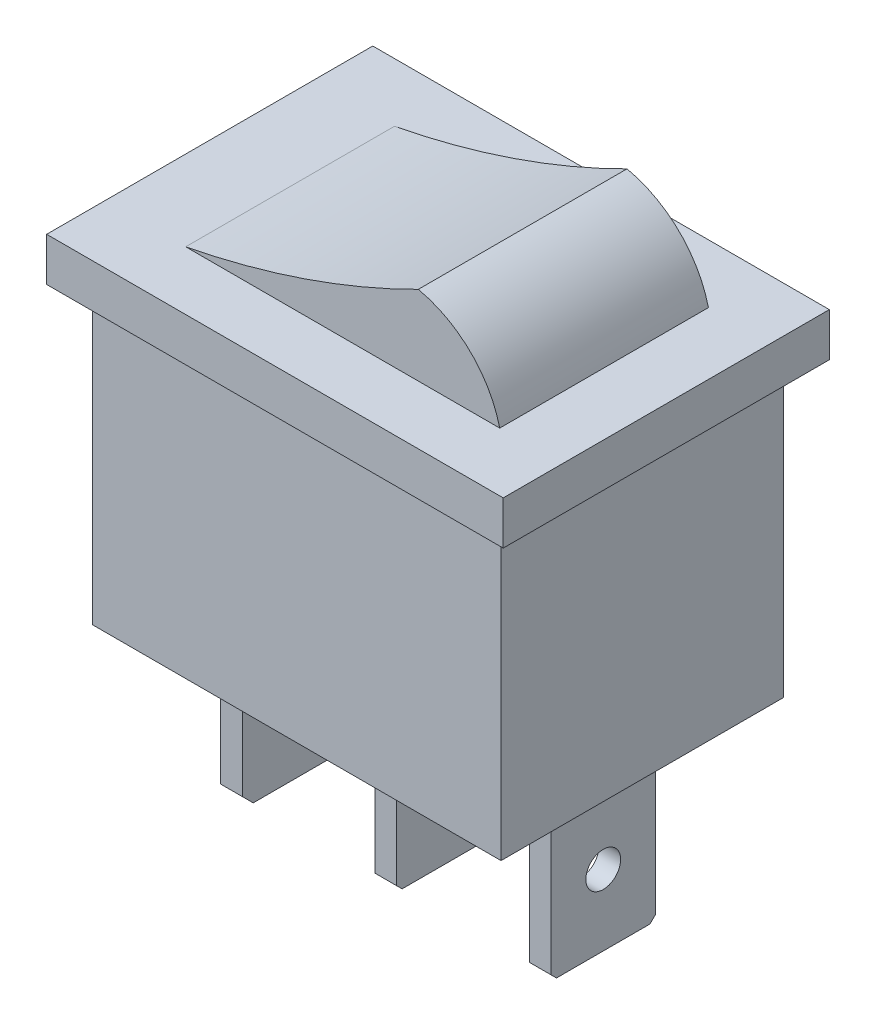
SolidWorks part; units mm, degrees
ref_plane "Front Plane" through (0, 0, 0) normal (0, 0, 1) x (1, 0, 0)
ref_plane "Top Plane" through (0, 0, 0) normal (0, 1, 0) x (1, 0, 0)
ref_plane "Right Plane" through (0, 0, 0) normal (1, 0, 0) x (0, 0, -1)
ref_plane "Plane4" through (0, 0, -4.8) normal (0, 0, -1) x (-1, 0, 0)
sketch "Sketch1" plane through (0, 0, -4.8) normal (0, 0, -1) x (-1, 0, 0)
  line L0 (-7.6394, 15.5) -> (6.8039, 15.5)
  arc A0 (-3.8941, 19.1536) -> (-7.6394, 15.5) centre (-2.8428, 14.3295) ccw
  arc A1 (6.8039, 15.5) -> (-3.8941, 19.1536) centre (14.6611, 55.995) cw
extrude "Boss-Extrude1" add sketch "Sketch1" against normal blind 9.6
ref_plane "Plane5" through (0, 15.5, 0) normal (0, 1, 0) x (1, 0, 0)
sketch "Sketch2" plane through (0, 15.5, 0) normal (0, 1, 0) x (1, 0, 0)
  line L0 (10.5, -7.5) -> (10.5, 7.5)
  line L1 (10.5, 7.5) -> (-10.5, 7.5)
  line L2 (-10.5, 7.5) -> (-10.5, -7.5)
  line L3 (-10.5, -7.5) -> (10.5, -7.5)
extrude "Boss-Extrude2" add sketch "Sketch2" against normal blind 2
sketch "Sketch3" plane through (0, 13.5, 0) normal (0, -1, 0) x (1, 0, 0)
  line L0 (9.4, 6.5) -> (9.4, -6.5)
  line L1 (9.4, -6.5) -> (-9.4, -6.5)
  line L2 (-9.4, -6.5) -> (-9.4, 6.5)
  line L3 (-9.4, 6.5) -> (9.4, 6.5)
extrude "Boss-Extrude3" add sketch "Sketch3" along normal blind 13.5
sketch "Sketch4" plane through (0, 0, 0) normal (0, -1, 0) x (1, 0, 0)
  line L0 (0.5, 2.4) -> (0.5, -2.4)
  line L1 (0.5, -2.4) -> (-0.5, -2.4)
  line L2 (-0.5, -2.4) -> (-0.5, 2.4)
  line L3 (-0.5, 2.4) -> (0.5, 2.4)
extrude "Boss-Extrude4" add sketch "Sketch4" along normal blind 8
sketch "Sketch5" plane through (0, 0, 0) normal (0, -1, 0) x (1, 0, 0)
  line L0 (7.6, 2.4) -> (7.6, -2.4)
  line L1 (7.6, -2.4) -> (6.6, -2.4)
  line L2 (6.6, -2.4) -> (6.6, 2.4)
  line L3 (6.6, 2.4) -> (7.6, 2.4)
extrude "Boss-Extrude5" add sketch "Sketch5" along normal blind 8
sketch "Sketch6" plane through (0, 0, 0) normal (0, -1, 0) x (1, 0, 0)
  line L0 (-6.6, -2.4) -> (-7.6, -2.4)
  line L1 (-7.6, -2.4) -> (-7.6, 2.4)
  line L2 (-7.6, 2.4) -> (-6.6, 2.4)
  line L3 (-6.6, 2.4) -> (-6.6, -2.4)
extrude "Boss-Extrude6" add sketch "Sketch6" along normal blind 8
hole_wizard "Ø1.6 (1.6) Diameter Hole1" positions "Sketch8" profile "Sketch7" hole size "Ø1.6" standard "ANSI Metric"
sketch "Sketch8" plane through (-7.6, 0, 0) normal (-1, 0, 0) x (0, 0, 1)
  point P0 (0, -4.5)
sketch "Sketch7" plane through (-7.6, -4.5, 0) normal (0, 1, 0) x (0, 0, 1)
  line L0 (0, 0) -> (0, 1)
  line L1 (0, 1) -> (0.8, 1)
  line L2 (0.8, 1) -> (0.8, 0)
  line L5 (0.8, 0) -> (0, 0)
  line L11 (0, -6.35) -> (0, 107.95) construction
  dimension "Thru Hole Dia." = 1.6
  dimension "Thru Hole Depth" = 1
hole_wizard "Ø1.6 (1.6) Diameter Hole2" positions "Sketch10" profile "Sketch9" hole size "Ø1.6" standard "ANSI Metric"
sketch "Sketch10" plane through (7.6, 0, 0) normal (1, 0, 0) x (0, 0, -1)
  point P0 (0, -4.5)
sketch "Sketch9" plane through (7.6, -4.5, 0) normal (0, 1, 0) x (0, 0, -1)
  line L0 (0, 0) -> (0, 1)
  line L1 (0, 1) -> (0.8, 1)
  line L2 (0.8, 1) -> (0.8, 0)
  line L5 (0.8, 0) -> (0, 0)
  line L11 (0, -6.35) -> (0, 107.95) construction
  dimension "Thru Hole Dia." = 1.6
  dimension "Thru Hole Depth" = 1
hole_wizard "Ø1.6 (1.6) Diameter Hole3" positions "Sketch12" profile "Sketch11" hole size "Ø1.6" standard "ANSI Metric"
sketch "Sketch12" plane through (-0.5, 0, 0) normal (-1, 0, 0) x (0, 0, 1)
  point P0 (0, -4.5)
sketch "Sketch11" plane through (-0.5, -4.5, 0) normal (0, 1, 0) x (0, 0, 1)
  line L0 (0, 0) -> (0, 11)
  line L1 (0, 11) -> (0.8, 11)
  line L2 (0.8, 11) -> (0.8, 0)
  line L5 (0.8, 0) -> (0, 0)
  line L11 (0, -6.35) -> (0, 107.95) construction
  dimension "Thru Hole Dia." = 1.6
  dimension "Thru Hole Depth" = 11
chamfer "Chamfer1" distance 0.25 angle 45 4 edges at (7.6, -8, 0) (0.5, -8, 0) (-0.5, -8, 0) (6.6, -8, 0)
chamfer "Chamfer2" distance 0.5 angle 45 6 edges at (7.1, -8, 2.4) (-7.1, -8, -2.4) (7.1, -8, -2.4) (0, -8, -2.4) (-7.1, -8, 2.4) (0, -8, 2.4)
